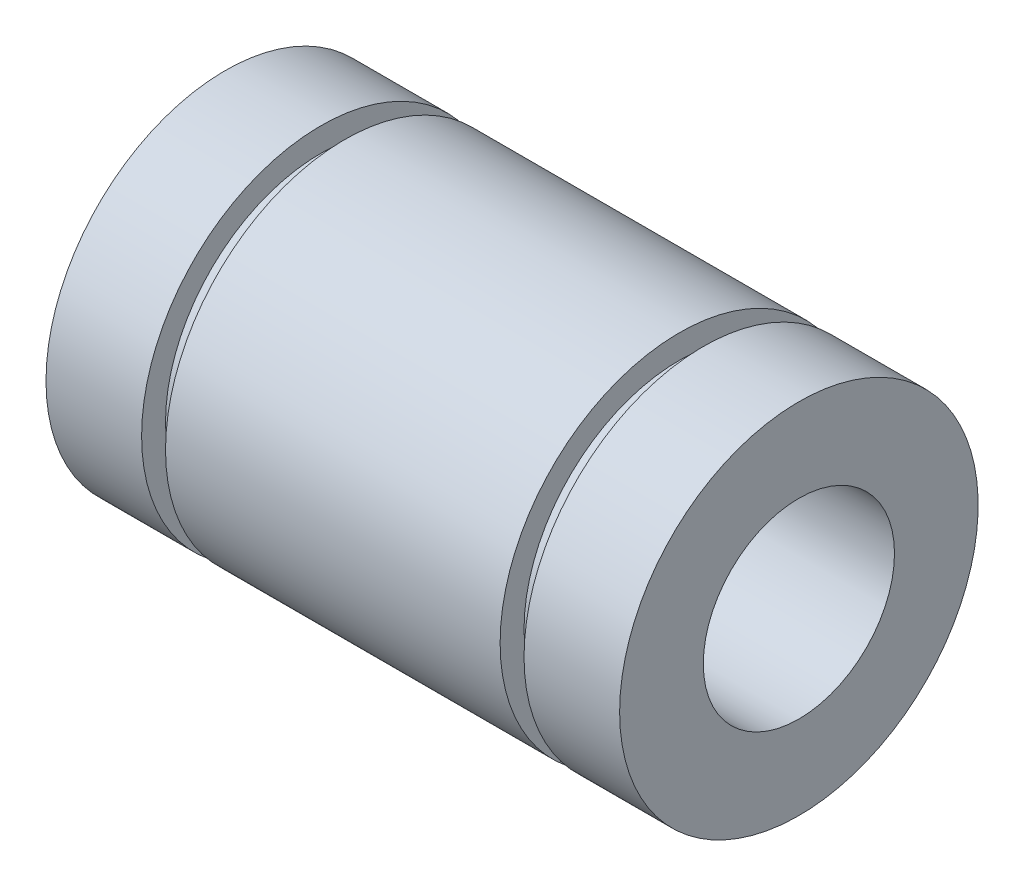
SolidWorks part; units mm, degrees
ref_plane "Plan de face" through (0, 0, 0) normal (0, 0, 1) x (1, 0, 0)
ref_plane "Plan de dessus" through (0, 0, 0) normal (0, 1, 0) x (1, 0, 0)
ref_plane "Plan de droite" through (0, 0, 0) normal (1, 0, 0) x (0, 0, -1)
sketch "Esquisse1" plane through (0, 0, 0) normal (0, 0, 1) x (1, 0, 0)
  line L0 (0, 4) -> (0, 7.5)
  line L1 (0, 7.5) -> (4, 7.5)
  line L2 (4, 7.5) -> (4, 6.5)
  line L3 (4, 6.5) -> (5, 6.5)
  line L4 (5, 6.5) -> (5, 7.5)
  line L5 (5, 7.5) -> (19, 7.5)
  line L6 (19, 7.5) -> (19, 6.5)
  line L7 (19, 6.5) -> (20, 6.5)
  line L8 (20, 6.5) -> (20, 7.5)
  line L9 (20, 7.5) -> (24, 7.5)
  line L10 (24, 7.5) -> (24, 4)
  line L11 (0, 0) -> (22.1886, 0) construction
  line L12 (0, 4) -> (24, 4)
  dimension "D1" = 4
  dimension "D2" = 7.5
  dimension "D3" = 24
  dimension "D4" = 4
  dimension "D5" = 4
  dimension "D6" = 1
  dimension "D7" = 1
  dimension "D8" = 7.5
  dimension "D9" = 7.5
  dimension "D10" = 13
  dimension "D11" = 13
revolve "Révolution1" add sketch "Esquisse1" angle 360 about L11
